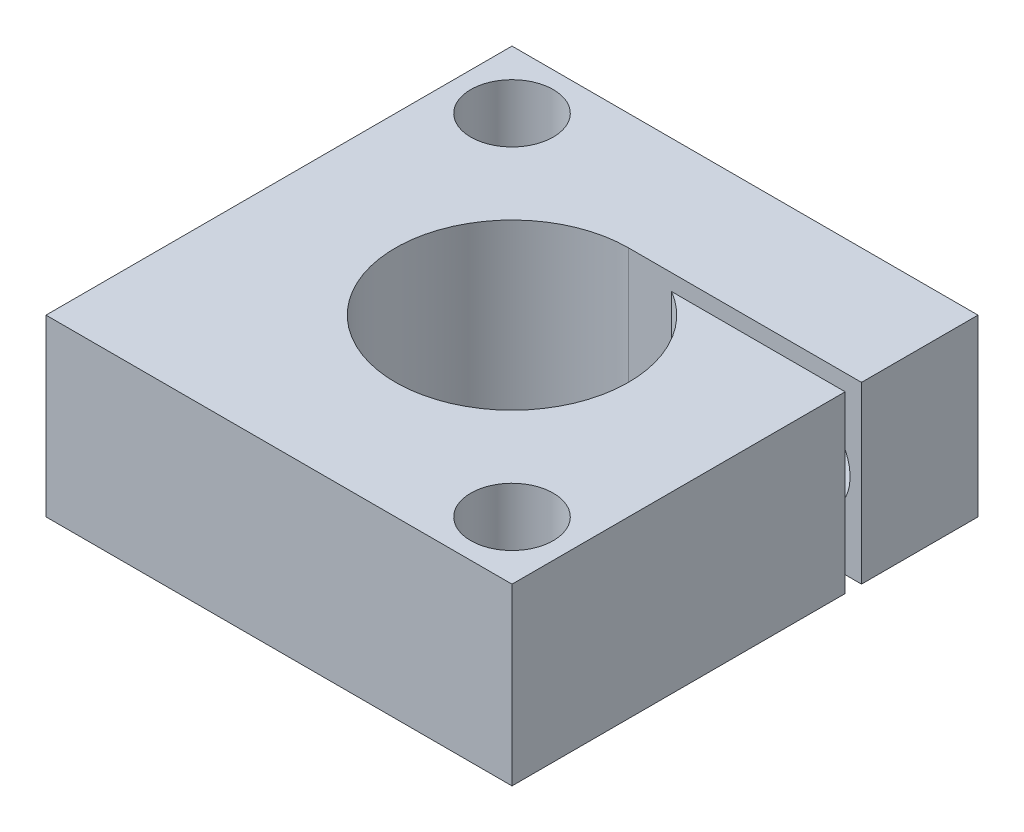
SolidWorks part; units mm, degrees
ref_plane "Front Plane" through (0, 0, 0) normal (0, 0, 1) x (1, 0, 0)
ref_plane "Top Plane" through (0, 0, 0) normal (0, 1, 0) x (1, 0, 0)
ref_plane "Right Plane" through (0, 0, 0) normal (1, 0, 0) x (0, 0, -1)
sketch "Sketch1" plane through (0, 0, 0) normal (0, 1, 0) x (1, 0, 0)
  line L0 (1.5006, 8.4813) -> (1.5006, -9.6797)
  line L1 (-11.1994, 9.3703) -> (1.5006, 9.3703)
  line L2 (-23.8994, 15.7203) -> (1.5006, 15.7203)
  line L3 (-23.8994, 15.7203) -> (-23.8994, -9.6797)
  line L4 (-23.8994, -9.6797) -> (1.5006, -9.6797)
  line L5 (1.5006, 15.7203) -> (1.5006, 9.3703)
  line L7 (-7.959, 8.4813) -> (1.5006, 8.4813)
  arc A0 (-11.1994, 9.3703) -> (-7.959, 8.4813) centre (-11.1994, 3.0203) ccw
  dimension "D3" = 12.7
  dimension "D4" = 12.7
  dimension "D5" = 12.7
  dimension "D1" = 25.4
  dimension "D2" = 25.4
  dimension "D6" = 0.889
extrude "Boss-Extrude1" add sketch "Sketch1" along normal blind 9.525
hole_wizard "#8 Clearance Hole1" positions "Sketch3" profile "Sketch2" hole size "#8" standard "ANSI Inch" end condition through all
sketch "Sketch3" plane through (0, 9.525, 0) normal (0, 1, 0) x (1, 0, 0)
  arc A0 (-11.1994, 9.3703) -> (-7.959, 8.4813) centre (-11.1994, 3.0203) ccw construction
  point P0 (-20.7244, 12.5453)
  point P2 (-1.6744, -6.5047)
  dimension "D3" = 9.525
  dimension "D4" = 9.525
  dimension "D1" = 9.525
  dimension "D2" = 9.525
sketch "Sketch2" plane through (-20.7244, 9.525, -12.5453) normal (1, 0, 0) x (0, 0, 1)
  line L0 (0, 0) -> (0, 9.525)
  line L1 (0, 9.525) -> (2.2479, 9.525)
  line L2 (2.2479, 9.525) -> (2.2479, 0)
  line L5 (2.2479, 0) -> (0, 0)
  line L11 (0, -6.35) -> (0, 107.95) construction
  dimension "Thru Hole Dia." = 4.4958
  dimension "Thru Hole Depth" = 9.525
hole_wizard "#10-24 Tapped Hole1" positions "Sketch5" profile "Sketch4" tap size "#10-24" standard "ANSI Inch"
sketch "Sketch5" plane through (0, 0, -8.4813) normal (0, 0, -1) x (-1, 0, 0)
  line L0 (-1.5006, 9.525) -> (-1.5006, 0) construction
  line L2 (-1.5006, 9.525) -> (23.8994, 9.525) construction
  point P0 (1.6744, 4.7625)
  dimension "D1" = 3.175
  dimension "D2" = 4.7625
sketch "Sketch4" plane through (-1.6744, 4.7625, -8.4813) normal (1, 0, 0) x (0, 1, 0)
  line L0 (0, 0) -> (0, 12.3168)
  line L1 (0, 12.3168) -> (1.8986, 11.176)
  line L2 (1.8986, 11.176) -> (1.8986, 0)
  line L5 (1.8986, 0) -> (0, 0)
  line L10 (0, 12.3168) -> (-1.8987, 11.176) construction
  line L11 (0, -6.35) -> (0, 107.95) construction
  dimension "Tap Drill Dia." = 3.7973
  dimension "Tap Drill Depth" = 11.176
  dimension "Drill Angle" = 118
cosmetic thread "Hole Thread3" parameters "D1"=8.89, "D2"=4.826
hole_wizard "#10 Clearance Hole1" positions "Sketch7" profile "Sketch8" hole size "#10" standard "ANSI Inch"
sketch "Sketch7" plane through (0, 0, -15.7203) normal (0, 0, -1) x (-1, 0, 0)
  line L0 (-1.5006, 0) -> (23.8994, 0) construction
  line L1 (-1.5006, 9.525) -> (-1.5006, 0) construction
  point P0 (1.6744, 4.7625)
  dimension "D1" = 4.7625
  dimension "D2" = 3.175
sketch "Sketch8" plane through (-1.6744, 4.7625, -15.7203) normal (1, 0, 0) x (0, 1, 0)
  line L0 (0, 0) -> (0, 6.35)
  line L1 (0, 6.35) -> (2.5527, 6.35)
  line L2 (2.5527, 6.35) -> (2.5527, 0)
  line L5 (2.5527, 0) -> (0, 0)
  line L11 (0, -6.35) -> (0, 107.95) construction
  dimension "Thru Hole Dia." = 5.1054
  dimension "Thru Hole Depth" = 6.35
